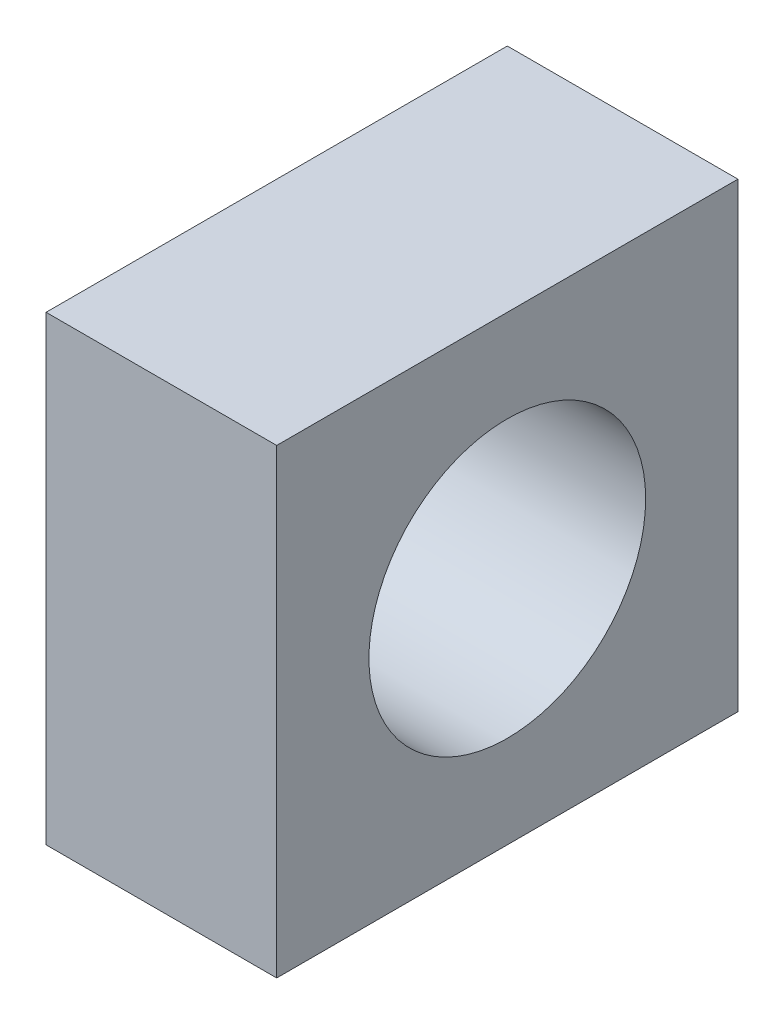
SolidWorks part; units mm, degrees
ref_plane "前视基准面" through (0, 0, 0) normal (0, 0, 1) x (1, 0, 0)
ref_plane "上视基准面" through (0, 0, 0) normal (0, 1, 0) x (1, 0, 0)
ref_plane "右视基准面" through (0, 0, 0) normal (1, 0, 0) x (0, 0, -1)
other "Configuration Table"
sketch "草图1" plane through (0, 0, 0) normal (1, 0, 0) x (0, 0, -1)
  line L5 (-1, -1) -> (1, 1) construction
  line L6 (-1, 1) -> (1, -1) construction
  line L7 (-1, 1) -> (1, 1)
  line L8 (-1, 1) -> (-1, -1)
  line L9 (-1, -1) -> (1, -1)
  line L10 (1, 1) -> (1, -1)
  circle A0 centre (0, 0) radius 0.6
  point P0 (0, 0)
  dimension "D1" = 1.2
  dimension "D3" = 2
extrude "凸台-拉伸2" add sketch "草图1" along normal blind 1
